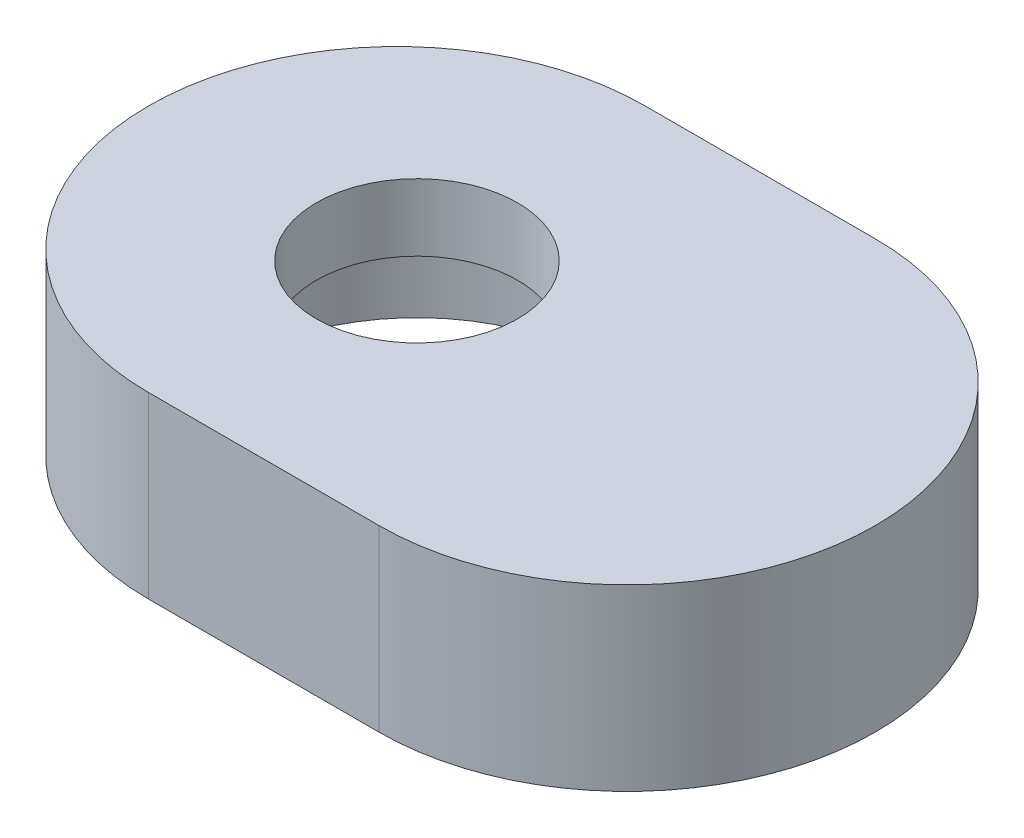
SolidWorks part; units mm, degrees
ref_plane "Front Plane" through (0, 0, 0) normal (0, 0, 1) x (1, 0, 0)
ref_plane "Top Plane" through (0, 0, 0) normal (0, 1, 0) x (1, 0, 0)
ref_plane "Right Plane" through (0, 0, 0) normal (1, 0, 0) x (0, 0, -1)
sketch "Sketch1" plane through (0, 0, 0) normal (0, 1, 0) x (1, 0, 0)
  line L0 (0, 0) -> (10.3, 0) construction
  line L1 (0, 11.1) -> (10.3, 11.1)
  line L2 (0, -11.1) -> (10.3, -11.1)
  arc A0 (0, 11.1) -> (0, -11.1) centre (0, 0) ccw
  arc A1 (10.3, -11.1) -> (10.3, 11.1) centre (10.3, 0) ccw
  circle A2 centre (0.9, 0) radius 8.2
  point P3 (5.15, 0)
  dimension "D2" = 32.5
  dimension "D3" = 16.4
  dimension "D1" = 22.2
  dimension "D4" = 12
extrude "Boss-Extrude1" add sketch "Sketch1" along normal blind 8
sketch "Sketch2" plane through (0, 8, 0) normal (0, 1, 0) x (1, 0, 0)
  circle A0 centre (0.9, 0) radius 8.2
  circle A1 centre (0.9, 0) radius 4.5
  circle A2 centre (0.9, 0) radius 8.2 construction
  dimension "D1" = 9
extrude "Boss-Extrude2" add sketch "Sketch2" against normal blind 3
